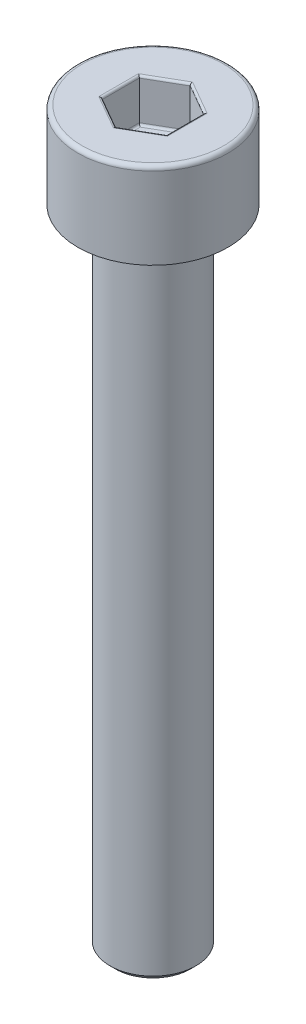
SolidWorks part; units mm, degrees
ref_plane "Front Plane" through (0, 0, 0) normal (0, 0, 1) x (1, 0, 0)
ref_plane "Top Plane" through (0, 0, 0) normal (0, 1, 0) x (1, 0, 0)
ref_plane "Right Plane" through (0, 0, 0) normal (1, 0, 0) x (0, 0, -1)
sketch "Sketch1" plane through (0, 0, 0) normal (0, 0, 1) x (1, 0, 0)
  line L0 (0, 0) -> (0, -47.0967) construction
  line L1 (0, -34) -> (-2, -34)
  line L2 (-2, -34) -> (-2, -4)
  line L3 (-2, -4) -> (-3.5, -4)
  line L4 (-3.5, -4) -> (-3.5, 0)
  line L5 (-3.5, 0) -> (0, 0)
  line L6 (0, 0) -> (0, -34)
  dimension "d" = 4
  dimension "l" = 34
  dimension "k" = 4
  dimension "dk" = 7
revolve "Revolve1" add sketch "Sketch1" angle 360 about L0
chamfer "Chamfer1" distance 0.25 angle 45 2 edges at (0, -4, 2) (0, -34, 2)
fillet "Fillet1" radius 0.2 1 edges at (0, 0, 3.5)
sketch "Sketch2" plane through (0, 0, 0) normal (0, 1, 0) x (1, 0, 0)
  line L1 (0, 1.7321) -> (-1.5, 0.866)
  line L2 (-1.5, 0.866) -> (-1.5, -0.866)
  line L3 (-1.5, -0.866) -> (0, -1.7321)
  line L4 (0, -1.7321) -> (1.5, -0.866)
  line L5 (1.5, -0.866) -> (1.5, 0.866)
  line L6 (1.5, 0.866) -> (0, 1.7321)
  circle A0 centre (0, 0) radius 1.5 construction
  dimension "s" = 3
extrude "Cut-Extrude1" cut sketch "Sketch2" against normal blind 2
fillet "Fillet2" radius 0.1 12 edges at (-0.75, 0, -1.299) (-1.5, 0, 0) (-0.75, 0, 1.299) (0.75, 0, 1.299) (1.5, 0, 0) (0.75, 0, -1.299) (1.5, -2, 0) (0.75, -2, 1.299) (-0.75, -2, 1.299) (-1.5, -2, 0) (-0.75, -2, -1.299) (0.75, -2, -1.299)
